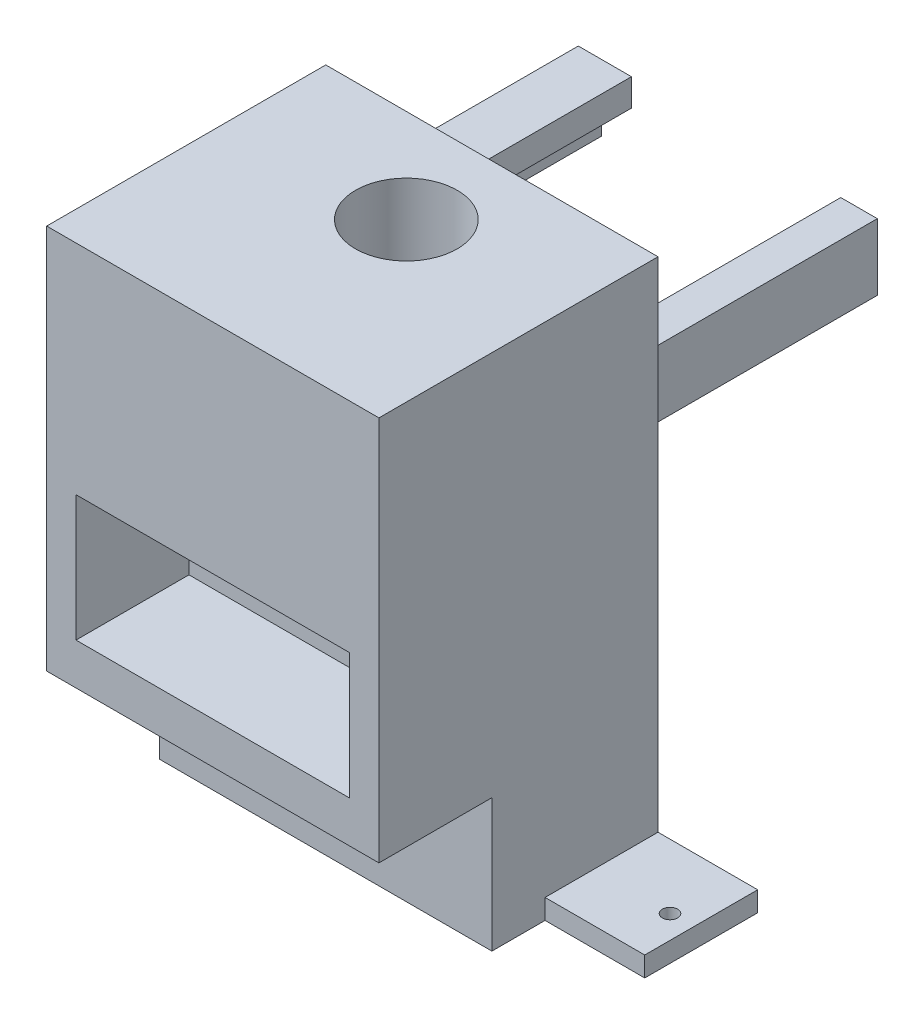
SolidWorks part; units mm, degrees
ref_plane "Front Plane" through (0, 0, 0) normal (0, 0, 1) x (1, 0, 0)
ref_plane "Top Plane" through (0, 0, 0) normal (0, 1, 0) x (1, 0, 0)
ref_plane "Right Plane" through (0, 0, 0) normal (1, 0, 0) x (0, 0, -1)
sketch "Sketch3" plane through (0, 0, 0) normal (0, 1, 0) x (1, 0, 0)
  line L0 (-1.2188, 24.4601) -> (-1.2188, 7.4601) construction
  line L1 (-41.2188, 24.4601) -> (38.7812, 24.4601)
  line L2 (-41.2188, 24.4601) -> (-41.2188, 7.4601)
  line L3 (-41.2188, 7.4601) -> (-26.2188, 7.4601)
  line L4 (38.7812, 24.4601) -> (38.7812, 7.4601)
  line L5 (23.7812, 7.4601) -> (38.7812, 7.4601)
  line L7 (-26.2188, 7.4601) -> (-26.2188, -0.5399)
  line L8 (-26.2188, -0.5399) -> (23.7812, -0.5399)
  line L9 (23.7812, 7.4601) -> (23.7812, -0.5399)
  dimension "D1" = 80
  dimension "D2" = 17
  dimension "D3" = 25
  dimension "D4" = 25
  dimension "D5" = 8
extrude "OG base" add sketch "Sketch3" along normal blind 3
sketch "Sketch5" plane through (0, 3, 0) normal (0, 1, 0) x (1, 0, 0)
  line L0 (-46.3557, 14.7608) -> (46.3536, 14.7608) construction
  line L1 (38.7812, 24.4601) -> (-41.2188, 24.4601) construction
  line L2 (-41.2188, 7.4601) -> (-26.2188, 7.4601) construction
  line L3 (-1.2188, 24.4601) -> (-1.2188, -0.5399) construction
  line L4 (-26.2188, -0.5399) -> (23.7812, -0.5399) construction
  line L5 (-37.7188, 24.4601) -> (-37.7188, 7.4601) construction
  line L6 (35.2812, 24.4601) -> (35.2812, 7.4601) construction
  line L7 (23.7812, 7.4601) -> (38.7812, 7.4601) construction
  circle A0 centre (-37.7188, 14.7608) radius 1.15
  circle A1 centre (35.2812, 14.7608) radius 1.15
  dimension "D5" = 2.3
  dimension "D6" = 2.3
  dimension "D1" = 9.6992
  dimension "D2" = 7.3008
  dimension "D3" = 36.5
  dimension "D4" = 36.5
extrude "Cut-Extrude1" cut sketch "Sketch5" against normal blind 3
sketch "Sketch6" plane through (0, 3, 0) normal (0, 1, 0) x (1, 0, 0)
  line L0 (38.7812, 24.4601) -> (-41.2188, 24.4601) construction
  line L1 (-26.2188, -0.5399) -> (23.7812, -0.5399)
  line L2 (-26.2188, -0.5399) -> (-26.2188, 24.4601)
  line L3 (-26.2188, 24.4601) -> (23.7812, 24.4601)
  line L4 (23.7812, -0.5399) -> (23.7812, 24.4601)
  dimension "D1" = 50
extrude "Boss-Extrude3" add sketch "Sketch6" along normal blind 75
sketch "Sketch8" plane through (-26.2188, 0, 0) normal (-1, 0, 0) x (0, 0, 1)
  line L0 (-27.4273, 0) -> (9.7555, 0) construction
  line L1 (0.5399, 20) -> (17.5399, 20)
  line L3 (17.5399, 20) -> (17.5399, 78)
  line L4 (0.5399, 78) -> (17.5399, 78)
  line L5 (0.5399, 78) -> (0.5399, 20)
  line L6 (0.5399, 78) -> (0.5399, 0) construction
  dimension "D1" = 20
extrude "Boss-Extrude4" add sketch "Sketch8" against normal blind 50
sketch "Sketch9" plane through (-26.2188, 0, 0) normal (-1, 0, 0) x (0, 0, 1)
  line L0 (-24.0483, 76.0909) -> (16.9517, 76.0909) construction
  line L1 (16.9517, 76.0909) -> (16.9517, 15.0909) construction
  line L2 (16.9517, 15.0909) -> (-24.0483, 15.0909) construction
  line L3 (-24.0483, 15.0909) -> (-24.0483, 76.0909) construction
  line L4 (10.3237, 16.7909) -> (16.4656, 16.7909) construction
  line L5 (15.2517, 20.1969) -> (15.2517, 15.8308) construction
  line L6 (15.3517, 75.3642) -> (15.3517, 67.5826) construction
  line L7 (10.9554, 74.8909) -> (16.3156, 74.8909) construction
  line L8 (-22.509, 16.8409) -> (-18.2333, 16.8409) construction
  line L9 (-22.3983, 21.3663) -> (-22.3983, 17.9249) construction
  line L10 (-22.3983, 16.8409) -> (-22.3983, 17.9249) construction
  line L11 (-22.9741, 74.7909) -> (-18.7427, 74.7909) construction
  line L12 (-22.3483, 75.7983) -> (-22.3483, 70.1702) construction
  circle A0 centre (-21.6983, 74.1409) radius 0.65
  circle A1 centre (14.7017, 74.2409) radius 0.65
  circle A2 centre (-21.7483, 17.4909) radius 0.65
  circle A3 centre (14.6017, 17.4409) radius 0.65
  dimension "D3" = 1.7
  dimension "D11" = 1.3
  dimension "D12" = 1.3
  dimension "D13" = 1.3
  dimension "D14" = 1.3
  dimension "D1" = 41
  dimension "D2" = 61
  dimension "D4" = 1.7
  dimension "D5" = 1.6
  dimension "D6" = 1.2
  dimension "D7" = 1.75
  dimension "D8" = 1.65
  dimension "D9" = 1.3
  dimension "D10" = 1.7
sketch "Sketch10" plane through (0, 0, -24.4601) normal (0, 0, -1) x (-1, 0, 0)
  line L0 (-38.7812, 0) -> (-46.8218, 0) construction
  line L1 (-46.8218, 60) -> (40.5526, 60) construction
  line L7 (-21.2812, 63.9656) -> (23.7188, 63.9656)
  line L8 (-21.2812, 63.9656) -> (-21.2812, 53.9656)
  line L9 (-21.2812, 53.9656) -> (23.7188, 53.9656)
  line L10 (23.7188, 63.9656) -> (23.7188, 53.9656)
  line L12 (-23.7812, 78) -> (-23.7812, 3) construction
  dimension "D1" = 60
  dimension "D2" = 45
  dimension "D3" = 2.5
  dimension "D4" = 10
extrude "Boss-Extrude5" add sketch "Sketch10" along normal blind 35.5
sketch "Sketch11" plane through (0, 0, -59.9601) normal (0, 0, -1) x (-1, 0, 0)
  line L0 (-38.7812, 0) -> (-54.1506, 0) construction
  line L1 (-21.2812, 58.9656) -> (-49.0495, 58.9656) construction
  line L2 (-21.2812, 63.9656) -> (-21.2812, 53.9656) construction
  line L3 (-21.2812, 58.9656) -> (23.7188, 58.9656) construction
  line L4 (23.7188, 53.9656) -> (23.7188, 63.9656) construction
  line L5 (1.2188, 63.9656) -> (1.2188, 53.9656) construction
  line L6 (23.7188, 63.9656) -> (-21.2812, 63.9656) construction
  line L7 (-21.2812, 53.9656) -> (23.7188, 53.9656) construction
  line L8 (-21.2812, 59.8656) -> (23.7188, 59.8656) construction
  line L9 (23.7188, 53.9656) -> (23.7188, 63.9656) construction
  line L10 (-21.2812, 58.0656) -> (23.7188, 58.0656) construction
  line L11 (-21.2812, 63.9656) -> (-21.2812, 53.9656) construction
  line L13 (-18.9112, 63.9656) -> (-18.9112, 53.9656) construction
  line L14 (21.3488, 63.9656) -> (21.3488, 53.9656) construction
  line L15 (-21.2812, 53.9656) -> (23.7188, 53.9656) construction
  line L16 (-17.7812, 53.9656) -> (-17.7812, 63.9656) construction
  line L17 (20.2188, 53.9656) -> (20.2188, 63.9656) construction
  line L18 (-15.7812, 53.9656) -> (-15.7812, 63.9656) construction
  line L19 (15.7188, 53.9656) -> (15.7188, 63.9656) construction
  line L20 (-18.9112, 59.8656) -> (21.3488, 59.8656)
  line L21 (-18.9112, 59.8656) -> (-18.9112, 58.0656)
  line L22 (-18.9112, 58.0656) -> (21.3488, 58.0656)
  line L23 (21.3488, 59.8656) -> (21.3488, 58.0656)
  dimension "D1" = 58.9656
  dimension "D2" = 0.9
  dimension "D3" = 0.9
  dimension "D4" = 20.13
  dimension "D5" = 20.13
  dimension "D6" = 3.5
  dimension "D7" = 3.5
  dimension "D8" = 5.5
  dimension "D9" = 8
extrude "Cut-Extrude2" cut sketch "Sketch11" against normal blind 40
sketch "Sketch13" plane through (0, 0, -59.9601) normal (0, 0, -1) x (-1, 0, 0)
  line L0 (-17.7812, 58.0656) -> (-17.7812, 53.9656)
  line L1 (-18.9112, 58.0656) -> (21.3488, 58.0656) construction
  line L2 (-17.7812, 53.9656) -> (-17.7812, 63.9656) construction
  line L3 (-17.7812, 53.9656) -> (20.2188, 53.9656)
  line L4 (20.2188, 53.9656) -> (20.2188, 58.0656)
  line L5 (20.2188, 53.9656) -> (20.2188, 63.9656) construction
  line L6 (20.2188, 58.0656) -> (-17.7812, 58.0656)
extrude "Cut-Extrude3" cut sketch "Sketch13" against normal blind 40
sketch "Sketch14" plane through (0, 0, -59.9601) normal (0, 0, -1) x (-1, 0, 0)
  line L0 (-15.7812, 63.9656) -> (-15.7812, 59.8656)
  line L1 (-18.9112, 59.8656) -> (21.3488, 59.8656) construction
  line L2 (-15.7812, 53.9656) -> (-15.7812, 63.9656) construction
  line L3 (-15.7812, 59.8656) -> (15.7188, 59.8656)
  line L4 (15.7188, 59.8656) -> (15.7188, 63.9656)
  line L5 (15.7188, 63.9656) -> (-15.7812, 63.9656)
  point P7 (15.7188, 48.2802)
  point P11 (15.7188, 52.3802)
  point P12 (0, 0)
  point P13 (0, 0)
  point P14 (15.7188, 48.2802)
extrude "Cut-Extrude4" cut sketch "Sketch14" against normal blind 40
sketch "Sketch20" plane through (0, 53.9656, 0) normal (0, 1, 0) x (1, 0, 0)
  line L0 (-20.0269, 20.054) -> (22.9701, 20.054) construction
sketch "Sketch19" plane through (0, 78, 0) normal (0, 1, 0) x (1, 0, 0)
  circle A0 centre (0, 10.3668) radius 7.65
  point P2 (0, 10.3668)
  dimension "D1" = 15.3
extrude "Cut-Extrude6" cut sketch "Sketch19" against normal blind 28
sketch "Sketch21" plane through (0, 0, 17.5399) normal (0, 0, 1) x (1, 0, 0)
  line L1 (-21.8076, 45.1971) -> (19.3701, 45.1971)
  line L2 (-21.8076, 45.1971) -> (-21.8076, 26.2472)
  line L3 (-21.8076, 26.2472) -> (19.3701, 26.2472)
  line L4 (19.3701, 45.1971) -> (19.3701, 26.2472)
extrude "Cut-Extrude7" cut sketch "Sketch21" against normal blind 17
